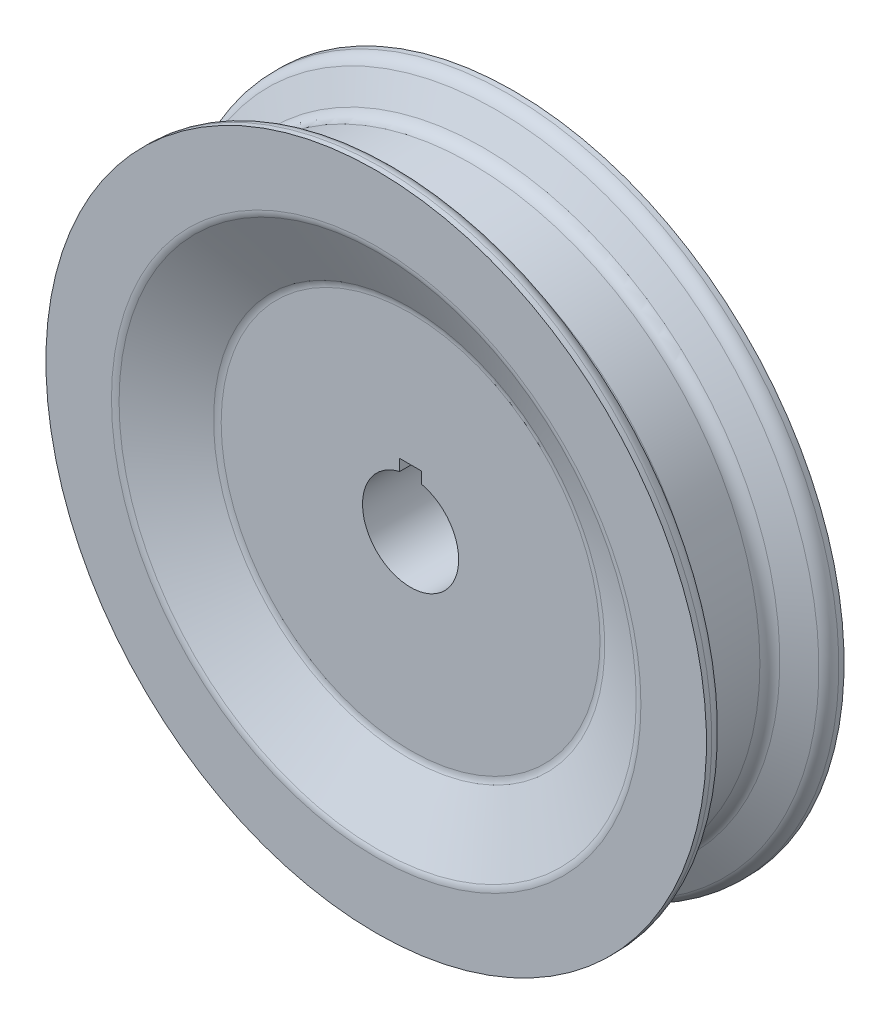
SolidWorks part; units mm, degrees
material "1023 Carbon Steel Sheet (SS)"
ref_plane "Front Plane" through (0, 0, 0) normal (0, 0, 1) x (1, 0, 0)
ref_plane "Top Plane" through (0, 0, 0) normal (0, 1, 0) x (1, 0, 0)
ref_plane "Right Plane" through (0, 0, 0) normal (1, 0, 0) x (0, 0, -1)
sketch "Sketch1" plane through (0, 0, 0) normal (1, 0, 0) x (0, 0, -1)
  line L0 (-25, 120) -> (-25, 95)
  line L1 (-12.5, 0) -> (12.5, 0)
  line L2 (25, 95) -> (25, 120)
  line L3 (-25, 120) -> (-20, 120)
  line L4 (-20, 120) -> (-12.5, 105)
  line L5 (-12.5, 105) -> (12.5, 105)
  line L6 (12.5, 105) -> (20, 120)
  line L7 (20, 120) -> (25, 120)
  line L8 (-25, 95) -> (-12.5, 70)
  line L9 (-12.5, 70) -> (-12.5, 0)
  line L10 (25, 95) -> (12.5, 70)
  line L11 (12.5, 70) -> (12.5, 0)
  point P2 (0, 0)
  point P6 (0, 105)
  dimension "D1" = 120
  dimension "D2" = 50
  dimension "D3" = 15
  dimension "D4" = 5
  dimension "D5" = 25
  dimension "D6" = 10
  dimension "D7" = 25
  dimension "D8" = 25
revolve "Main wheel extrude" add sketch "Sketch1" angle 360 about L1
fillet "Fillets" radius 5 8 edges at (0, -95, 25) (0, -70, 12.5) (0, -95, -25) (0, -70, -12.5) (0, -105, 12.5) (0, -105, -12.5) (0, -120, 20) (0, -120, -20)
sketch "Sketch3" plane through (0, 0, -12.5) normal (0, 0, -1) x (-1, 0, 0)
  line L0 (-3.9688, 17.0055) -> (-3.9688, 21.1381)
  line L1 (-3.9688, 21.1381) -> (3.9688, 21.1381)
  line L2 (3.9688, 21.1381) -> (3.9688, 17.0055)
  arc A0 (-3.9688, 17.0055) -> (3.9688, 17.0055) centre (0, 0) ccw
  point P5 (0, 21.1381)
  dimension "D1" = 34.925
  dimension "D2" = 4.1326
  dimension "D3" = 7.9375
extrude "Shaft cut" cut sketch "Sketch3" against normal through all both and the other way through all
